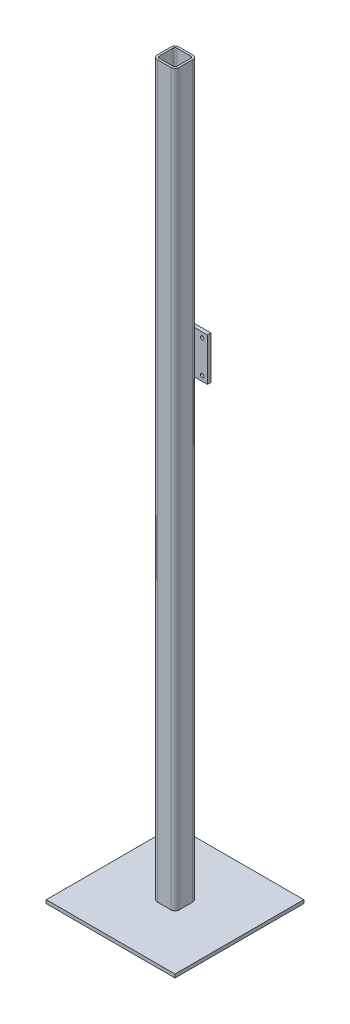
SolidWorks part; units mm, degrees
ref_plane "Płaszczyzna przednia" through (0, 0, 0) normal (0, 0, 1) x (1, 0, 0)
ref_plane "Płaszczyzna górna" through (0, 0, 0) normal (0, 1, 0) x (1, 0, 0)
ref_plane "Płaszczyzna prawa" through (0, 0, 0) normal (1, 0, 0) x (0, 0, -1)
sketch3d "Szkic 3D1"
  line L0 (0, 0, 0) -> (0, 1700, 0)
  dimension "D1" = 1700
other "Rura cienkościenna kwadratowa TS2X2X0.1875(1)"
ref_plane "Płaszczyzna1" through (0, 0, 0) normal (0, 1, 0) x (1, 0, 0)
sketch "Sketch12" plane through (0, 0, 0) normal (0, 1, 0) x (1, 0, 0)
  line L0 (-15.875, -20.6375) -> (15.875, -20.6375)
  line L1 (-20.6375, -15.875) -> (-20.6375, 15.875)
  line L2 (15.875, 20.6375) -> (-15.875, 20.6375)
  line L3 (20.6375, 15.875) -> (20.6375, -15.875)
  line L4 (-15.875, -25.4) -> (15.875, -25.4)
  line L5 (-25.4, -15.875) -> (-25.4, 15.875)
  line L6 (15.875, 25.4) -> (-15.875, 25.4)
  line L7 (25.4, 15.875) -> (25.4, -15.875)
  line L8 (-25.4, 0) -> (-20.6375, 0) construction
  line L9 (-20.6375, 0) -> (20.6375, 0) construction
  line L10 (20.6375, 0) -> (25.4, 0) construction
  line L11 (0, 25.4) -> (0, 20.6375) construction
  line L12 (0, 20.6375) -> (0, -20.6375) construction
  line L13 (0, -20.6375) -> (0, -25.4) construction
  arc A0 (25.4, 15.875) -> (15.875, 25.4) centre (15.875, 15.875) ccw
  arc A1 (15.875, -25.4) -> (25.4, -15.875) centre (15.875, -15.875) ccw
  arc A2 (-25.4, -15.875) -> (-15.875, -25.4) centre (-15.875, -15.875) ccw
  arc A3 (-15.875, 25.4) -> (-25.4, 15.875) centre (-15.875, 15.875) ccw
  arc A4 (-15.875, 20.6375) -> (-20.6375, 15.875) centre (-15.875, 15.875) ccw
  arc A5 (20.6375, 15.875) -> (15.875, 20.6375) centre (15.875, 15.875) ccw
  arc A6 (15.875, -20.6375) -> (20.6375, -15.875) centre (15.875, -15.875) ccw
  arc A7 (-20.6375, -15.875) -> (-15.875, -20.6375) centre (-15.875, -15.875) ccw
  point P6 (-25.4, -25.4)
  point P33 (-25.4, 25.4)
  point P35 (25.4, 25.4)
  point P36 (25.4, -25.4)
  point P37 (0, 0)
  point P38 (0, 0)
  dimension "D1" = 9.525
  dimension "Thickness" = 4.7625
  dimension "V_leg" = 50.8
  dimension "H_leg" = 50.8
sketch "Szkic5" plane through (0, 0, 0) normal (0, -1, 0) x (1, 0, 0)
  line L1 (-150, 150) -> (150, 150)
  line L2 (-150, 150) -> (-150, -150)
  line L3 (-150, -150) -> (150, -150)
  line L4 (150, 150) -> (150, -150)
  line L5 (-150, 150) -> (150, -150) construction
  line L6 (-150, -150) -> (150, 150) construction
  point P0 (0, 0)
  dimension "D1" = 300
  dimension "D2" = 300
extrude "Dodanie-wyciągnięcie1" add sketch "Szkic5" along normal blind 8 separate body
sketch "Szkic6" plane through (0, 0, -25.4) normal (0, 0, -1) x (-1, 0, 0)
  line L0 (150, -8) -> (-150, -8) construction
  line L1 (-50, 1152) -> (50, 1152)
  line L2 (-50, 1152) -> (-50, 1052)
  line L3 (-50, 1052) -> (50, 1052)
  line L4 (50, 1152) -> (50, 1052)
  line L5 (-50, 1152) -> (50, 1052) construction
  line L6 (-50, 1052) -> (50, 1152) construction
  circle A0 centre (-38, 1140) radius 4.1
  circle A1 centre (38, 1140) radius 4.1
  circle A2 centre (38, 1064) radius 4.1
  circle A3 centre (-38, 1064) radius 4.1
  point P0 (0, 1102)
  dimension "D4" = 8.2
  dimension "D1" = 100
  dimension "D2" = 100
  dimension "D3" = 1110
  dimension "D5" = 12
  dimension "D6" = 12
  dimension "D7" = 2
  dimension "D8" = 2
extrude "Dodanie-wyciągnięcie2" add sketch "Szkic6" along normal blind 8 separate body
